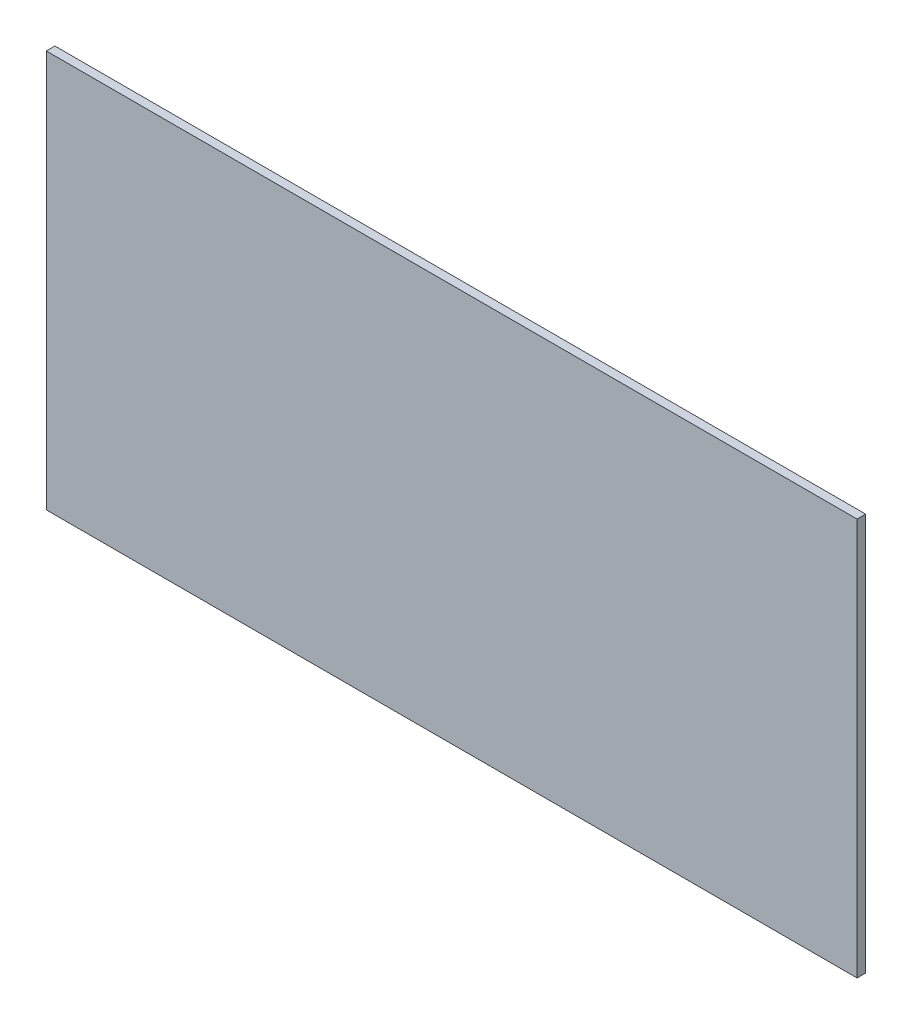
SolidWorks part; units mm, degrees
ref_plane "Front Plane" through (0, 0, 0) normal (0, 0, 1) x (1, 0, 0)
ref_plane "Top Plane" through (0, 0, 0) normal (0, 1, 0) x (1, 0, 0)
ref_plane "Right Plane" through (0, 0, 0) normal (1, 0, 0) x (0, 0, -1)
sketch "Sketch2" plane through (0, 0, 0) normal (0, 0, 1) x (1, 0, 0)
  line L1 (51, -25) -> (-51, -25)
  line L2 (51, -25) -> (51, 25)
  line L3 (51, 25) -> (-51, 25)
  line L4 (-51, -25) -> (-51, 25)
  line L5 (51, -25) -> (-51, 25) construction
  line L6 (51, 25) -> (-51, -25) construction
  point P0 (0, 0)
  dimension "D1" = 50
  dimension "D2" = 102
extrude "Boss-Extrude1" add sketch "Sketch2" along normal blind 1.08
